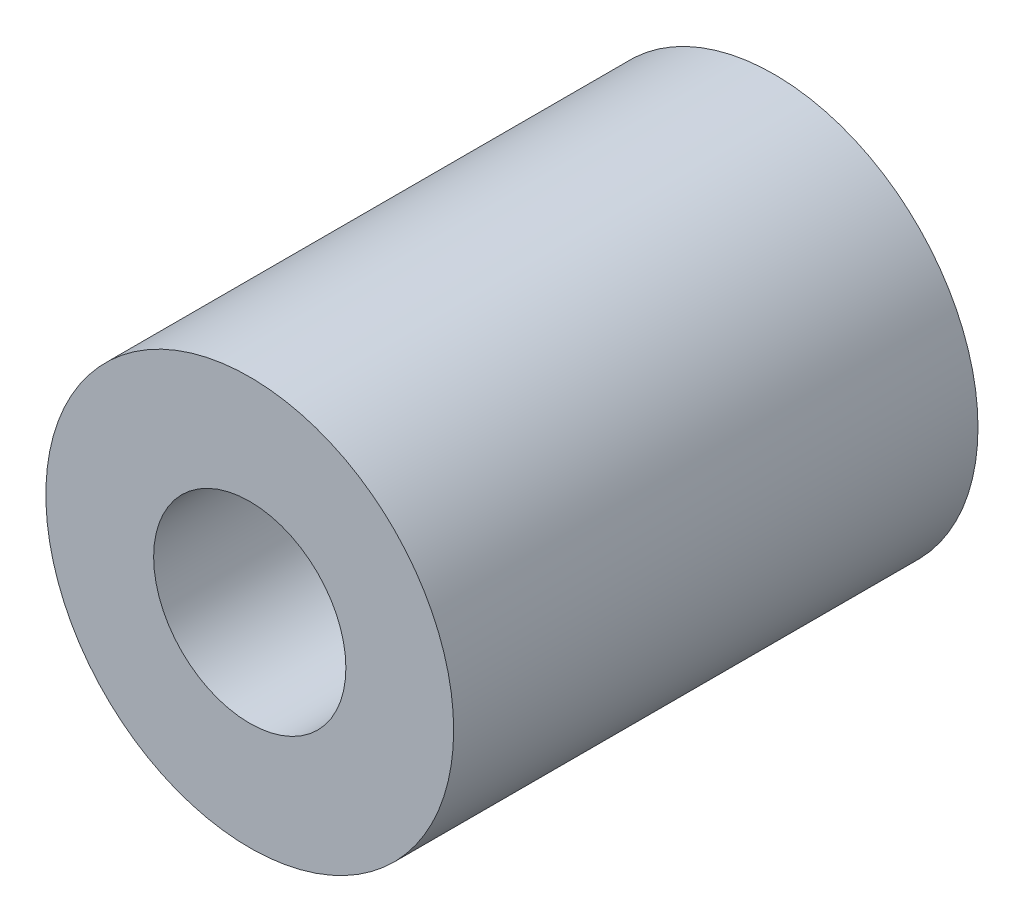
SolidWorks part; units mm, degrees
material "6061 合金"
ref_plane "前视基准面" through (0, 0, 0) normal (0, 0, 1) x (1, 0, 0)
ref_plane "上视基准面" through (0, 0, 0) normal (0, 1, 0) x (1, 0, 0)
ref_plane "右视基准面" through (0, 0, 0) normal (1, 0, 0) x (0, 0, -1)
sketch "草图1" plane through (0, 0, 0) normal (0, 0, 1) x (1, 0, 0)
  circle A1 centre (0, 0) radius 3.5
  dimension "D1" = 7
extrude "凸台-拉伸1" add sketch "草图1" along normal blind 9
hole_wizard "M4 螺纹孔1" positions "草图2" profile "草图3" tap size "M4" standard "GB" end condition through all
sketch "草图2" plane through (0, 0, 9) normal (0, 0, 1) x (1, 0, 0)
  point P0 (0, 0)
sketch "草图3" plane through (0, 0, 9) normal (1, 0, 0) x (0, -1, 0)
  line L0 (0, 0) -> (0, 9)
  line L1 (0, 9) -> (1.65, 9)
  line L2 (1.65, 9) -> (1.65, 0)
  line L5 (1.65, 0) -> (0, 0)
  line L11 (0, -6.35) -> (0, 107.95) construction
  dimension "通孔螺纹孔钻头直径" = 3.3
  dimension "通孔螺纹孔钻头深度" = 9
cosmetic thread "孔螺蚊线1" parameters "D2"=4
